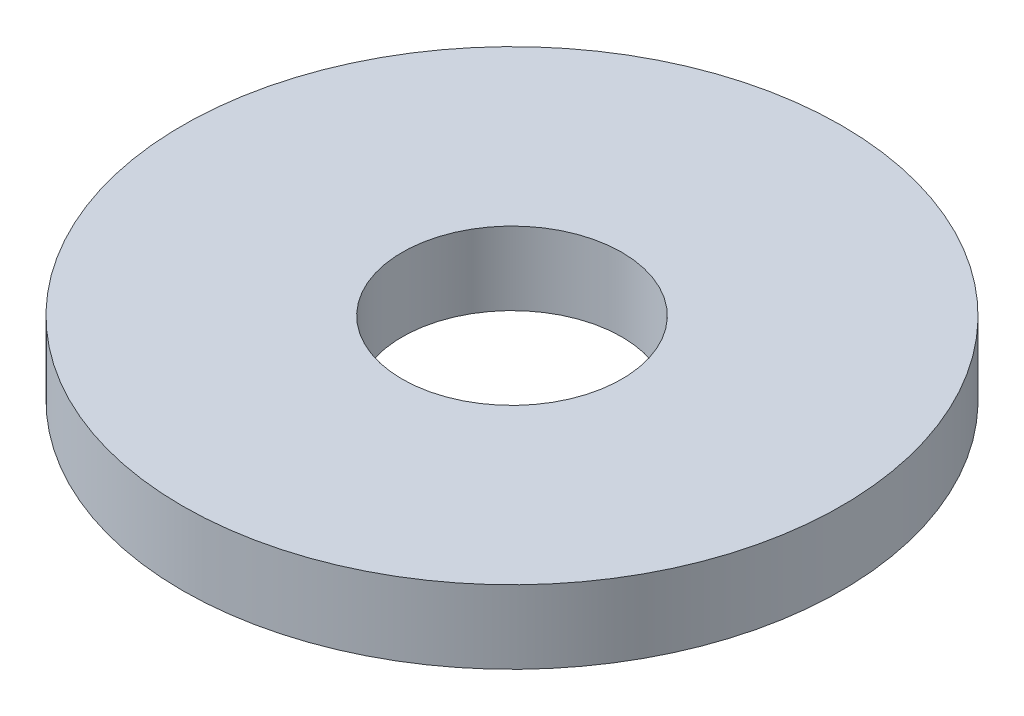
SolidWorks part; units mm, degrees
ref_plane "Alzado" through (0, 0, 0) normal (0, 0, 1) x (1, 0, 0)
ref_plane "Planta" through (0, 0, 0) normal (0, 1, 0) x (1, 0, 0)
ref_plane "Vista lateral" through (0, 0, 0) normal (1, 0, 0) x (0, 0, -1)
sketch "Croquis1" plane through (0, 0, 0) normal (0, 1, 0) x (1, 0, 0)
  circle A0 centre (0, 0) radius 4.5
  circle A1 centre (0, 0) radius 1.5
  dimension "D1" = 9
  dimension "D2" = 3
extrude "Saliente-Extruir1" add sketch "Croquis1" along normal blind 1
